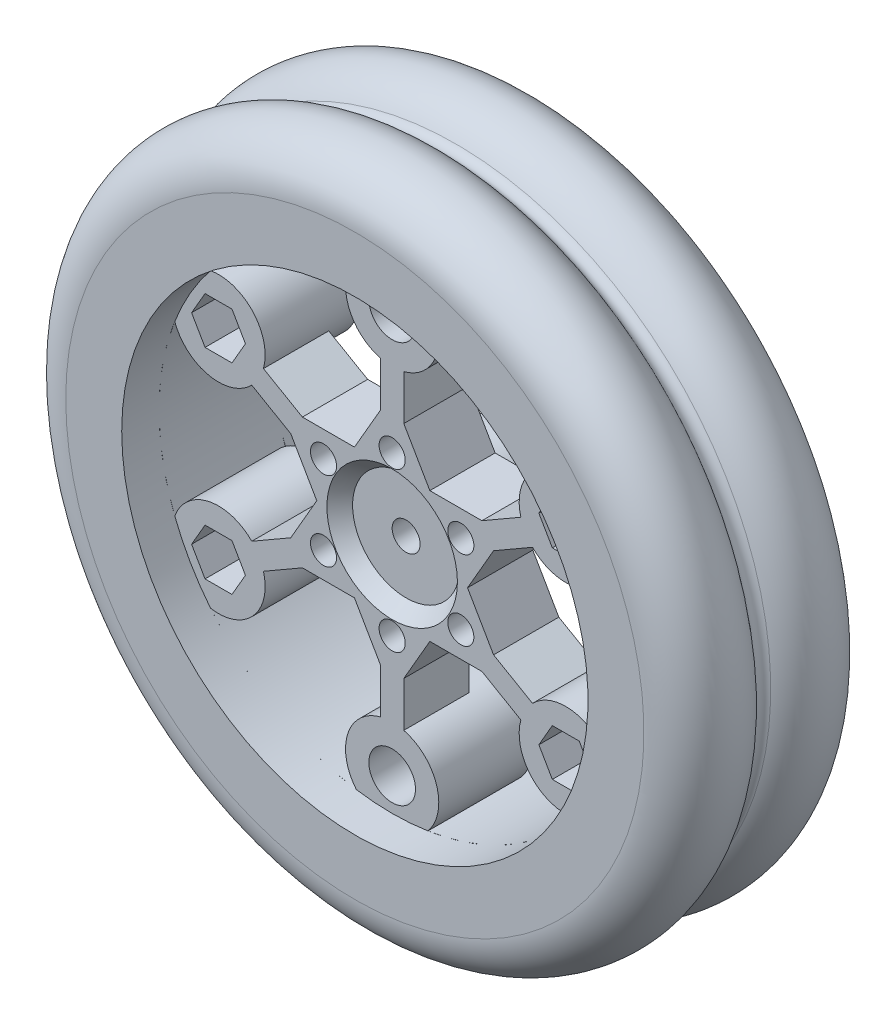
SolidWorks part; units mm, degrees
material "尼龙 6/10"
ref_plane "前视基准面" through (0, 0, 0) normal (0, 0, 1) x (1, 0, 0)
ref_plane "上视基准面" through (0, 0, 0) normal (0, 1, 0) x (1, 0, 0)
ref_plane "右视基准面" through (0, 0, 0) normal (1, 0, 0) x (0, 0, -1)
sketch "草图1" plane through (0, 0, 0) normal (0, 1, 0) x (1, 0, 0)
  line L0 (25, 10) -> (25, -10)
  line L1 (0, 146.934) -> (0, -105.6267) construction
  line L2 (25, 10) -> (31, 10)
  line L3 (25, -10) -> (31, -10)
  line L4 (-236.5493, 0) -> (326.6118, 0) construction
  arc A0 (33.7639, 0.8333) -> (31, 10) centre (31, 5) ccw
  arc A1 (33.7639, 0.8333) -> (33.7639, -0.8333) centre (34.3166, 0) ccw
  arc A2 (31, -10) -> (33.7639, -0.8333) centre (31, -5) ccw
  point P15 (31, 0)
  dimension "D4" = 1
  dimension "D1" = 20
  dimension "D2" = 25
  dimension "D3" = 31
revolve "旋转1" add sketch "草图1" angle 360 about L1
ref_plane "基准面1" through (0, 0, 6) normal (0, 0, 1) x (1, 0, 0)
sketch "草图2" plane through (0, 0, 6) normal (0, 0, 1) x (1, 0, 0)
  line L0 (0, 38.7462) -> (0, -39.0495) construction
  circle A0 centre (0, 0) radius 21.5 construction
  circle A1 centre (0, 21.5) radius 5
  dimension "D1" = 43
  dimension "D2" = 10
extrude "凸台-拉伸1" add sketch "草图2" against normal blind 10
pattern_circular "阵列(圆周)1" count 6 over 360 about axis through (0, 0, 0) along (0, 0, 1) of "凸台-拉伸1"
sketch "草图3" plane through (0, 0, 6) normal (0, 0, 1) x (1, 0, 0)
  line L0 (-8.0829, 0) -> (-10.8744, -4.8349)
  line L1 (0, 14) -> (-12.1244, 7) construction
  line L2 (-12.1244, 7) -> (-12.1244, -7) construction
  line L3 (-12.1244, -7) -> (0, -14) construction
  line L4 (0, -14) -> (12.1244, -7) construction
  line L5 (12.1244, -7) -> (12.1244, 7) construction
  line L6 (12.1244, 7) -> (0, 14) construction
  line L7 (-9.6244, -7) -> (-4.0415, -7)
  line L8 (10.8744, -4.8349) -> (8.0829, 0)
  line L9 (9.6244, 7) -> (4.0415, 7)
  line L10 (-10.8744, 4.8349) -> (-8.0829, 0)
  line L11 (-4.0415, -7) -> (-1.25, -11.8349)
  line L12 (0, 43.2923) -> (0, -38.3052) construction
  line L13 (-1.25, 16.6588) -> (-1.25, 11.8349)
  line L14 (1.25, 11.8349) -> (1.25, 16.6588)
  line L15 (10.8744, 4.8349) -> (15.0519, 7.2469)
  line L16 (13.8019, 9.4119) -> (9.6244, 7)
  line L17 (9.6244, -7) -> (13.8019, -9.4119)
  line L18 (15.0519, -7.2469) -> (10.8744, -4.8349)
  line L19 (-1.25, -11.8349) -> (-1.25, -16.6588)
  line L20 (1.25, -16.6588) -> (1.25, -11.8349)
  line L21 (-10.8744, -4.8349) -> (-15.0519, -7.2469)
  line L22 (-13.8019, -9.4119) -> (-9.6244, -7)
  line L23 (-9.6244, 7) -> (-13.8019, 9.4119)
  line L24 (-15.0519, 7.2469) -> (-10.8744, 4.8349)
  line L25 (-1.25, 11.8349) -> (-4.0415, 7)
  line L26 (1.25, -11.8349) -> (4.0415, -7)
  line L27 (4.0415, -7) -> (9.6244, -7)
  line L28 (-4.0415, 7) -> (-9.6244, 7)
  line L29 (4.0415, 7) -> (1.25, 11.8349)
  line L30 (8.0829, 0) -> (10.8744, 4.8349)
  circle A0 centre (0, 0) radius 12.1244 construction
  arc A1 (-3.839, 24.7035) -> (3.839, 24.7035) centre (0, 21.5) ccw construction
  arc A2 (-1.25, 16.6588) -> (1.25, 16.6588) centre (0, 21.5) ccw
  arc A3 (-23.3133, 9.0271) -> (-19.4744, 15.6764) centre (-18.6195, 10.75) ccw construction
  arc A4 (-19.4744, -15.6764) -> (-23.3133, -9.0271) centre (-18.6195, -10.75) ccw construction
  arc A5 (3.839, -24.7035) -> (-3.839, -24.7035) centre (0, -21.5) ccw construction
  arc A6 (23.3133, -9.0271) -> (19.4744, -15.6764) centre (18.6195, -10.75) ccw construction
  arc A7 (19.4744, 15.6764) -> (23.3133, 9.0271) centre (18.6195, 10.75) ccw construction
  arc A8 (-15.0519, 7.2469) -> (-13.8019, 9.4119) centre (-18.6195, 10.75) ccw
  arc A9 (-13.8019, -9.4119) -> (-15.0519, -7.2469) centre (-18.6195, -10.75) ccw
  arc A10 (1.25, -16.6588) -> (-1.25, -16.6588) centre (0, -21.5) ccw
  arc A11 (15.0519, -7.2469) -> (13.8019, -9.4119) centre (18.6195, -10.75) ccw
  arc A12 (13.8019, 9.4119) -> (15.0519, 7.2469) centre (18.6195, 10.75) ccw
  point P41 (0, 0)
  dimension "D1" = 28
  dimension "D2" = 2.5
  dimension "D3" = 6
extrude "凸台-拉伸2" add sketch "草图3" against normal blind 7
sketch "草图4" plane through (0, 0, -1) normal (0, 0, -1) x (-1, 0, 0)
  line L0 (0, 15.11) -> (0, -12.4392) construction
  circle A0 centre (0, 0) radius 8.5 construction
  circle A1 centre (0, 8.5) radius 1.4
  dimension "D1" = 17
  dimension "D2" = 2.8
extrude "切除-拉伸1" cut sketch "草图4" against normal through all
pattern_circular "阵列(圆周)2" count 6 over 360 about axis through (0, 0, 0) along (0, 0, 1) of "切除-拉伸1"
sketch "草图5" plane through (0, 0, -1) normal (0, 0, -1) x (-1, 0, 0)
  circle A0 centre (0, 0) radius 5.5
  dimension "D1" = 11
extrude "凸台-拉伸3" add sketch "草图5" along normal blind 5
sketch "草图7" plane through (0, 0, 6) normal (0, 0, 1) x (1, 0, 0)
  circle A0 centre (0, 0) radius 7
  dimension "D1" = 14
extrude "切除-拉伸3" cut sketch "草图7" against normal blind 1.5 draft 40
sketch "草图8" plane through (0, 0, 4.5) normal (0, 0, 1) x (1, 0, 0)
  circle A0 centre (0, 0) radius 1.5
  dimension "D1" = 3
extrude "切除-拉伸4" cut sketch "草图8" against normal through all
sketch "草图9" plane through (0, 0, -6) normal (0, 0, -1) x (-1, 0, 0)
  line L1 (3.5, 0) -> (1.75, 3.0311)
  line L2 (3.5, 0) -> (1.75, -3.0311)
  line L3 (1.75, -3.0311) -> (-1.75, -3.0311)
  line L4 (-3.5, 0) -> (-1.75, -3.0311)
  line L5 (1.75, 3.0311) -> (-1.75, 3.0311)
  line L6 (-3.5, 0) -> (-1.75, 3.0311)
sketch "草图10" plane through (0, 0, 6) normal (0, 0, 1) x (1, 0, 0)
  circle A0 centre (0, 21.5) radius 1.25
  dimension "D1" = 2.5
extrude "切除-拉伸6" cut sketch "草图10" against normal through all
pattern_circular "阵列(圆周)3" count 6 over 360 about axis through (0, 0, 0) along (0, 0, 1) of "切除-拉伸6"
sketch "草图11" plane through (0, 0, 6) normal (0, 0, 1) x (1, 0, 0)
  circle A0 centre (0, 21.5) radius 2.5
  dimension "D1" = 5
extrude "切除-拉伸7" cut sketch "草图11" against normal through all
pattern_circular "阵列(圆周)4" count 2 over 360 about axis through (0, 0, 0) along (0, 0, 1) of "切除-拉伸7"
sketch "草图12" plane through (0, 0, 6) normal (0, 0, 1) x (1, 0, 0)
  line L1 (20.0629, 8.25) -> (21.5063, 10.75)
  line L2 (21.5063, 10.75) -> (20.0629, 13.25)
  line L3 (20.0629, 13.25) -> (17.1762, 13.25)
  line L4 (17.1762, 13.25) -> (15.7328, 10.75)
  line L5 (15.7328, 10.75) -> (17.1762, 8.25)
  line L6 (17.1762, 8.25) -> (20.0629, 8.25)
  circle A0 centre (18.6195, 10.75) radius 2.5 construction
  dimension "D1" = 5
extrude "切除-拉伸8" cut sketch "草图12" against normal blind 8
pattern_circular "阵列(圆周)5" count 6 over 360 about axis through (0, 0, 0) along (0, 0, 1) skipping 2, 5 of "切除-拉伸8"
sketch "草图13" plane through (0, 0, 0) normal (0, 1, 0) x (1, 0, 0)
  line L0 (0, 19.3352) -> (0, -18.3764) construction
  line L1 (21, 6) -> (26, 6)
  line L2 (26, 6) -> (26, -6)
  line L3 (26, -6) -> (21, -6)
  line L4 (-6.1819, 0) -> (35.4823, 0) construction
  dimension "D1" = 26
  dimension "D2" = 12
  dimension "D3" = 5
surface "曲面-旋转1" sketch "草图13" parameters "D1"=360
surface "曲面-剪裁2"
extrude "切除-拉伸9" cut sketch "草图9" against normal blind 8
